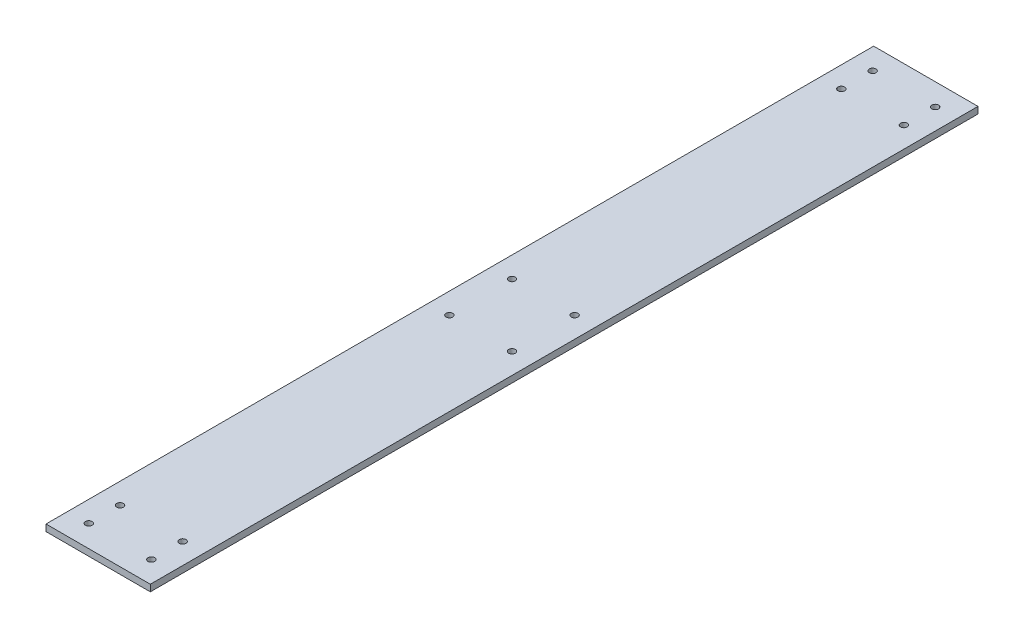
SolidWorks part; units mm, degrees
material "Acrylic (Medium-high impact)"
ref_plane "Front Plane" through (0, 0, 0) normal (0, 0, 1) x (1, 0, 0)
ref_plane "Top Plane" through (0, 0, 0) normal (0, 1, 0) x (1, 0, 0)
ref_plane "Right Plane" through (0, 0, 0) normal (1, 0, 0) x (0, 0, -1)
sketch "Sketch1" plane through (0, 0, 0) normal (0, 1, 0) x (1, 0, 0)
  line L1 (-25, 198.325) -> (25, 198.325)
  line L2 (-25, 198.325) -> (-25, -198.325)
  line L3 (-25, -198.325) -> (25, -198.325)
  line L4 (25, 198.325) -> (25, -198.325)
  line L5 (-25, 198.325) -> (25, -198.325) construction
  line L6 (-25, -198.325) -> (25, 198.325) construction
  point P0 (0, 0)
  dimension "D1" = 50
  dimension "D2" = 396.65
extrude "Boss-Extrude1" add sketch "Sketch1" along normal blind 3.175 contours L2 L3 L4 L1
hole_wizard "M3 Clearance Hole1" positions "Sketch3" profile "Sketch4" hole size "M3" standard "ANSI Metric" end condition through all
sketch "Sketch3" plane through (0, 0, 0) normal (0, -1, 0) x (-1, 0, 0)
  line L1 (-15, -172.825) -> (15, -172.825)
  line L2 (-15, -172.825) -> (-15, -187.825)
  line L3 (-15, -187.825) -> (15, -187.825)
  line L4 (15, -172.825) -> (15, -187.825)
  line L5 (-15, -172.825) -> (15, -187.825) construction
  line L6 (-15, -187.825) -> (15, -172.825) construction
  line L7 (25, -198.325) -> (-25, -198.325) construction
  point P2 (15, -187.825)
  point P39 (-15, -172.825)
  point P40 (-15, -187.825)
  point P41 (15, -172.825)
  point P44 (0, -180.325)
  point P51 (0, 0)
  dimension "D1" = 30
  dimension "D2" = 15
  dimension "D3" = 18
sketch "Sketch4" plane through (-15, 0, 187.825) normal (1, 0, 0) x (0, 0, -1)
  line L0 (0, 0) -> (0, 3.175)
  line L1 (0, 3.175) -> (1.6, 3.175)
  line L2 (1.6, 3.175) -> (1.6, 0)
  line L5 (1.6, 0) -> (0, 0)
  line L11 (0, -6.35) -> (0, 107.95) construction
  dimension "Thru Hole Dia." = 3.2
  dimension "Thru Hole Depth" = 3.175
ref_plane "Plane1" through (0, 0, 0) normal (0, 0, 1) x (1, 0, 0)
mirror "Mirror1" about plane through (0, 0, 0) normal (0, 0, 1) of "M3 Clearance Hole1"
hole_wizard "M3 Clearance Hole2" positions "Sketch5" profile "Sketch6" hole size "M3" standard "ANSI Metric" end condition through all
sketch "Sketch5" plane through (0, 0, 0) normal (0, -1, 0) x (-1, 0, 0)
  line L1 (-15, 15) -> (15, 15)
  line L2 (-15, 15) -> (-15, -15)
  line L3 (-15, -15) -> (15, -15)
  line L4 (15, 15) -> (15, -15)
  line L5 (-15, 15) -> (15, -15) construction
  line L6 (-15, -15) -> (15, 15) construction
  point P2 (15, -15)
  point P25 (-15, 15)
  point P26 (-15, -15)
  point P27 (15, 15)
  point P31 (0, 0)
  dimension "D1" = 30
  dimension "D2" = 30
sketch "Sketch6" plane through (-15, 0, 15) normal (1, 0, 0) x (0, 0, -1)
  line L0 (0, 0) -> (0, 3.175)
  line L1 (0, 3.175) -> (1.6, 3.175)
  line L2 (1.6, 3.175) -> (1.6, 0)
  line L5 (1.6, 0) -> (0, 0)
  line L11 (0, -6.35) -> (0, 107.95) construction
  dimension "Thru Hole Dia." = 3.2
  dimension "Thru Hole Depth" = 3.175
